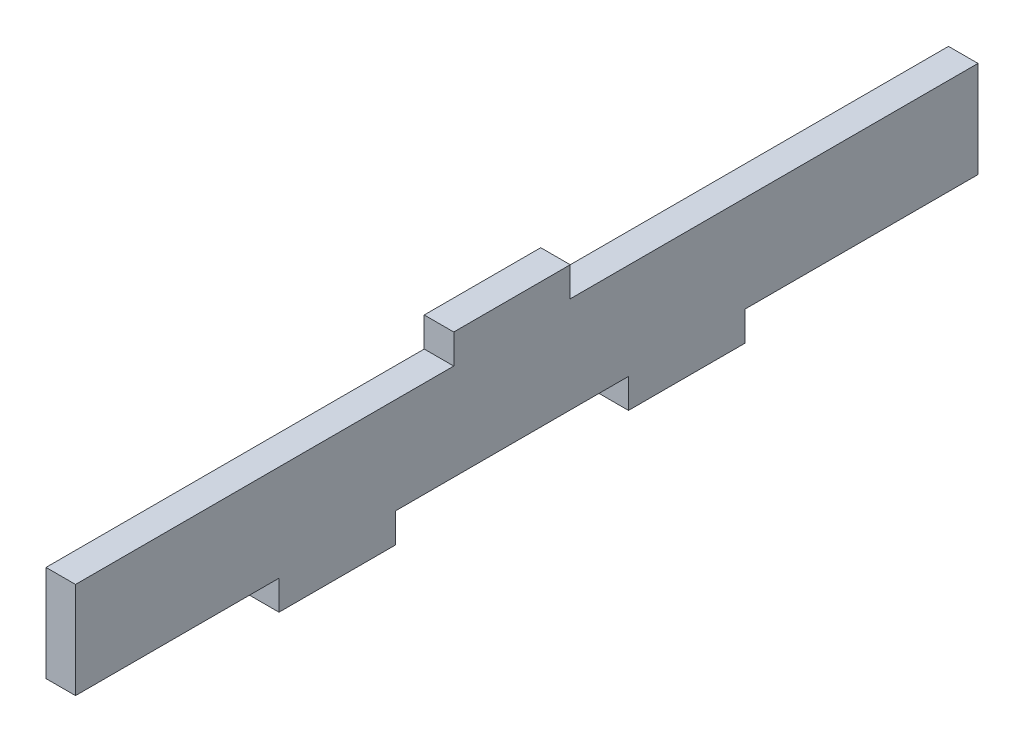
SolidWorks part; units mm, degrees
ref_plane "Front Plane" through (0, 0, 0) normal (0, 0, 1) x (1, 0, 0)
ref_plane "Top Plane" through (0, 0, 0) normal (0, 1, 0) x (1, 0, 0)
ref_plane "Right Plane" through (0, 0, 0) normal (1, 0, 0) x (0, 0, -1)
sketch "Sketch1" plane through (0, 0, 0) normal (1, 0, 0) x (0, 0, -1)
  line L1 (0, 0) -> (152.4, 0)
  line L2 (0, 0) -> (0, 25.4)
  line L3 (0, 25.4) -> (152.4, 25.4)
  line L4 (152.4, 0) -> (152.4, 25.4)
  dimension "D1" = 25.4
  dimension "D2" = 152.4
extrude "Boss-Extrude1" add sketch "Sketch1" along normal blind 4.826
sketch "Sketch2" plane through (4.826, 0, 0) normal (1, 0, 0) x (0, 0, -1)
  line L1 (0, 0) -> (152.4, 0) construction
  line L2 (0, 0) -> (38.1, 0)
  line L3 (0, 0) -> (0, 4.826)
  line L4 (0, 4.826) -> (38.1, 4.826)
  line L5 (38.1, 0) -> (38.1, 4.826)
  line L6 (57.15, 0) -> (95.25, 0)
  line L7 (57.15, 0) -> (57.15, 4.826)
  line L8 (57.15, 4.826) -> (95.25, 4.826)
  line L9 (95.25, 0) -> (95.25, 4.826)
  line L11 (38.1, 4.826) -> (57.15, 4.826) construction
  line L12 (152.4, 0) -> (114.3, 0)
  line L14 (152.4, 0) -> (152.4, 4.826)
  line L15 (152.4, 4.826) -> (114.3, 4.826)
  line L16 (114.3, 0) -> (114.3, 4.826)
  line L17 (95.25, 4.826) -> (114.3, 4.826) construction
  dimension "D1" = 19.05
  dimension "D2" = 4.826
extrude "Bottom Edge Slots" cut sketch "Sketch2" against normal through all
sketch "Sketch4" plane through (4.826, 0, 0) normal (1, 0, 0) x (0, 0, -1)
  line L0 (66.675, 20.574) -> (85.725, 20.574) construction
  line L1 (0, 25.4) -> (66.675, 25.4)
  line L2 (0, 25.4) -> (0, 20.574)
  line L3 (0, 20.574) -> (66.675, 20.574)
  line L4 (66.675, 25.4) -> (66.675, 20.574)
  line L5 (152.4, 25.4) -> (85.725, 25.4)
  line L6 (152.4, 25.4) -> (152.4, 20.574)
  line L7 (152.4, 20.574) -> (85.725, 20.574)
  line L8 (85.725, 25.4) -> (85.725, 20.574)
  dimension "D1" = 19.05
  dimension "D2" = 4.826
extrude "Top Edge Slot" cut sketch "Sketch4" against normal through all
sketch "Sketch6" plane through (4.826, 0, 0) normal (1, 0, 0) x (0, 0, -1)
  line L0 (0, 20.574) -> (66.675, 20.574) construction
  line L1 (0, 4.826) -> (4.826, 4.826)
  line L2 (0, 4.826) -> (0, 20.574)
  line L3 (0, 20.574) -> (4.826, 20.574)
  line L4 (4.826, 4.826) -> (4.826, 20.574)
  dimension "D1" = 4.826
extrude "Leading Edge Cut" cut sketch "Sketch6" against normal through all
equation "\"material\"= \"gmaterial@Forklift_Assembly.assembly\""
equation "\"D1@Boss-Extrude1\"=\"material\""
equation "\"D2@Sketch2\"=\"material\""
equation "\"D2@Sketch4\"=\"material\""
